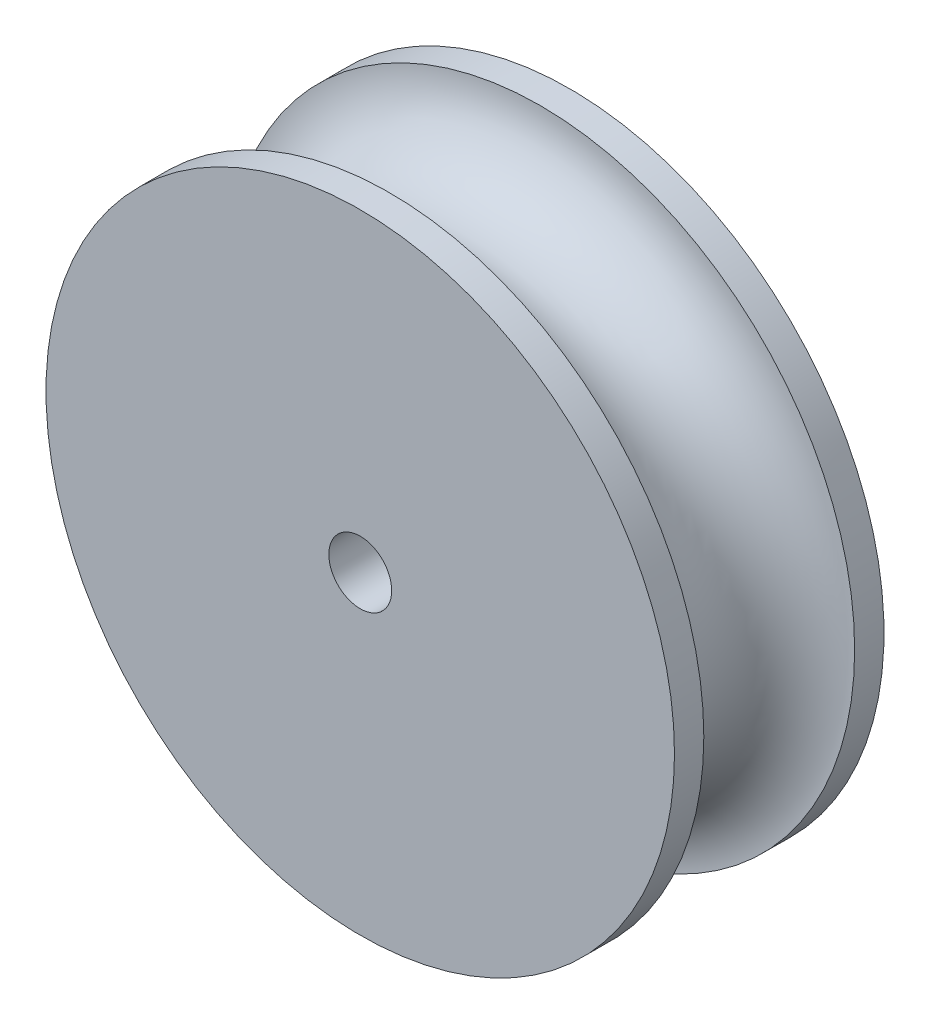
SolidWorks part; units mm, degrees
ref_plane "Front Plane" through (0, 0, 0) normal (0, 0, 1) x (1, 0, 0)
ref_plane "Top Plane" through (0, 0, 0) normal (0, 1, 0) x (1, 0, 0)
ref_plane "Right Plane" through (0, 0, 0) normal (1, 0, 0) x (0, 0, -1)
sketch "Sketch5" plane through (0, 0, 0) normal (0, 1, 0) x (1, 0, 0)
  line L0 (0, 0) -> (-38.1, 0)
  line L1 (-55, 0) -> (55, 0) construction
  line L2 (0, 0) -> (0, 18.288)
  line L3 (0, -55) -> (0, 55) construction
  line L4 (-38.1, 18.288) -> (0, 18.288)
  line L5 (0, 0) -> (0, 18.288) construction
  arc A0 (-38.1, 18.288) -> (-38.1, 0) centre (-38.1, 9.144) cw
  dimension "D1" = 38.1
  dimension "D2" = 18.288
revolve "Revolve1" add sketch "Sketch5" angle 360 about L5
sketch "Sketch9" plane through (0, 0, 0) normal (0, 0, 1) x (1, 0, 0)
  circle A0 centre (0, 0) radius 38.1
extrude "Boss-Extrude2" add sketch "Sketch9" along normal blind 3.556
sketch "Sketch10" plane through (0, 0, -18.288) normal (0, 0, -1) x (-1, 0, 0)
  circle A0 centre (0, 0) radius 38.1
extrude "Boss-Extrude3" add sketch "Sketch10" along normal blind 3.556
hole_wizard "3/4 (0.3) Diameter Hole1" positions "Sketch13" profile "Sketch14" hole size "3/4" standard "ANSI Inch" end condition through all
sketch "Sketch13" plane through (0, 0, 3.556) normal (0, 0, 1) x (1, 0, 0)
  point P0 (0, 0)
sketch "Sketch14" plane through (0, 0, 3.556) normal (1, 0, 0) x (0, -1, 0)
  line L0 (0, 0) -> (0, 25.4)
  line L1 (0, 25.4) -> (3.81, 25.4)
  line L2 (3.81, 25.4) -> (3.81, 0)
  line L5 (3.81, 0) -> (0, 0)
  line L11 (0, -6.35) -> (0, 107.95) construction
  dimension "Thru Hole Dia." = 7.62
  dimension "Thru Hole Depth" = 25.4
